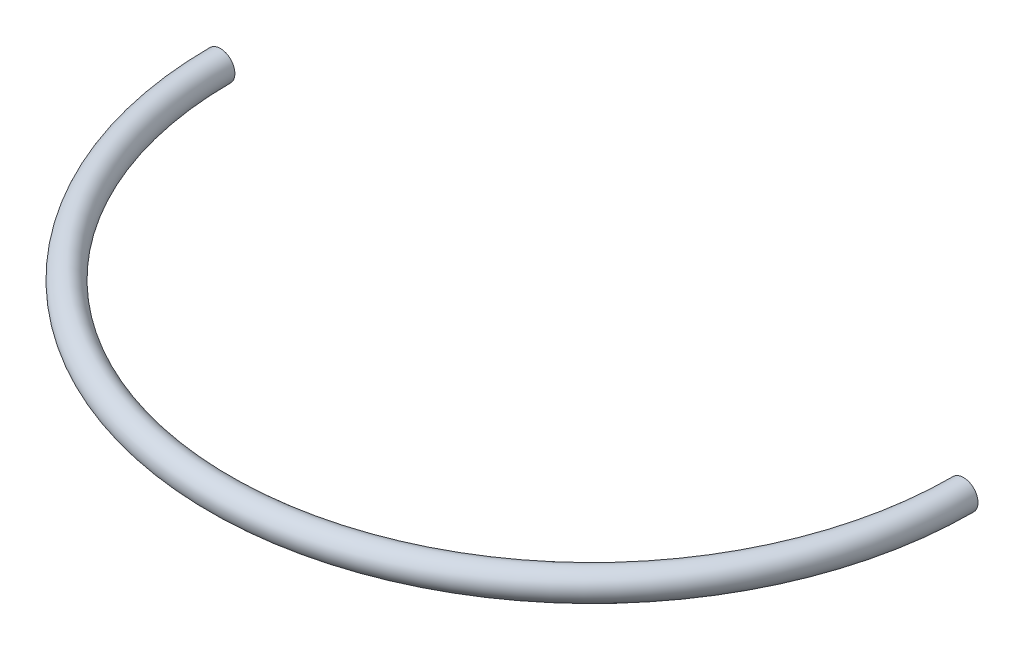
SolidWorks part; units mm, degrees
ref_plane "Front Plane" through (0, 0, 0) normal (0, 0, 1) x (1, 0, 0)
ref_plane "Top Plane" through (0, 0, 0) normal (0, 1, 0) x (1, 0, 0)
ref_plane "Right Plane" through (0, 0, 0) normal (1, 0, 0) x (0, 0, -1)
sketch "Sketch1" plane through (0, 0, 0) normal (0, 0, 1) x (1, 0, 0)
  circle A0 centre (-64, 0) radius 2.5
  dimension "D1" = 64
  dimension "D2" = 5
sketch "Sketch2" plane through (0, 0, 0) normal (0, 1, 0) x (1, 0, 0)
  arc A0 (64, 0) -> (-64, 0) centre (0, 0) cw
  dimension "D2" = 64
sweep "Sweep1" add profiles "Sketch1" path "Sketch2"
